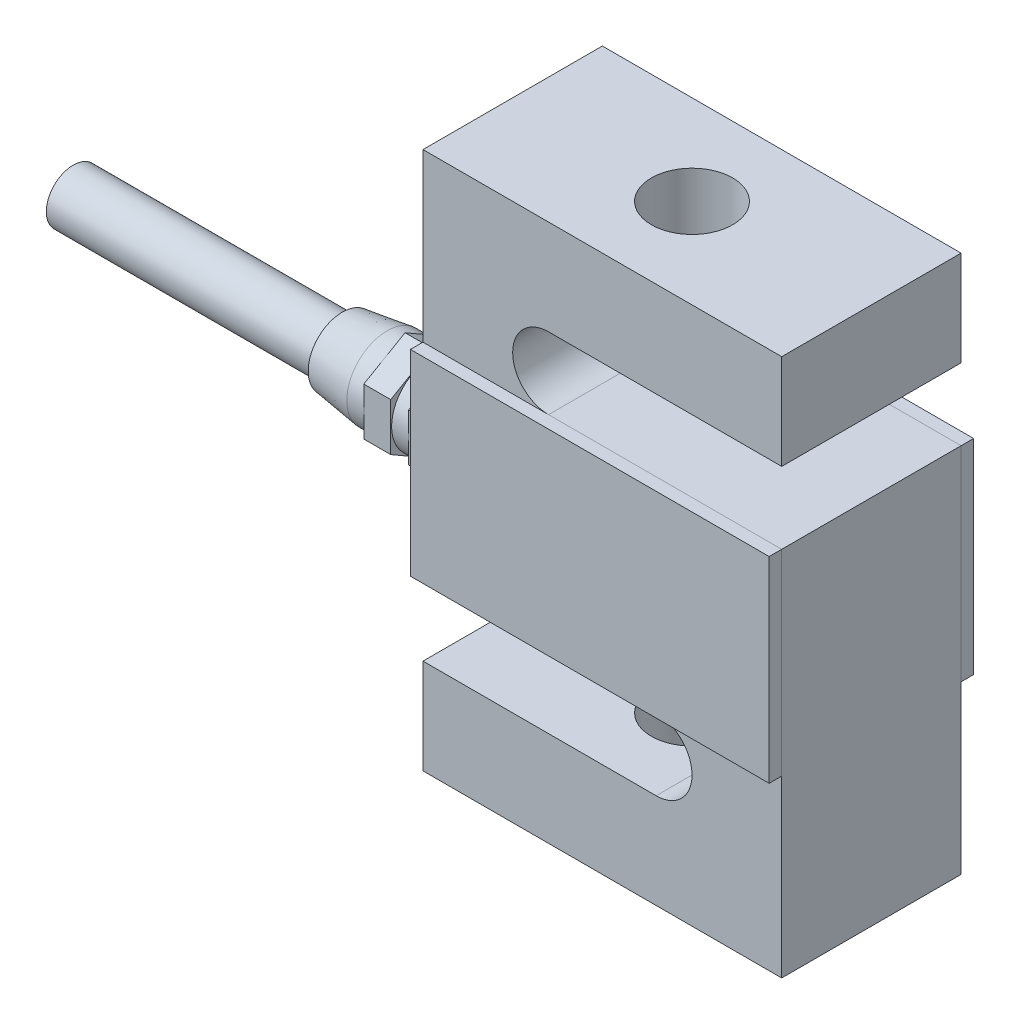
SolidWorks part; units mm, degrees
ref_plane "Front Plane" through (0, 0, 0) normal (0, 0, 1) x (1, 0, 0)
ref_plane "Top Plane" through (0, 0, 0) normal (0, 1, 0) x (1, 0, 0)
ref_plane "Right Plane" through (0, 0, 0) normal (1, 0, 0) x (0, 0, -1)
sketch "Sketch1" plane through (0, 0, 0) normal (0, 0, 1) x (1, 0, 0)
  line L0 (-25.4, -38.1) -> (25.4, -38.1)
  line L1 (25.4, -38.1) -> (25.4, 14.478)
  line L2 (25.4, 38.1) -> (-25.4, 38.1)
  line L3 (-25.4, 38.1) -> (-25.4, -14.478)
  line L4 (-25.4, -14.478) -> (7.62, -14.478)
  line L5 (-25.4, -24.638) -> (7.62, -24.638)
  line L6 (-69.5262, 0) -> (58.1333, 0) construction
  line L7 (7.62, -14.478) -> (7.62, -24.638) construction
  line L8 (-25.4, -24.638) -> (-25.4, -38.1)
  line L9 (-7.62, 24.638) -> (25.4, 24.638)
  line L10 (-7.62, 14.478) -> (25.4, 14.478)
  line L11 (25.4, 24.638) -> (25.4, 38.1)
  line L12 (-7.62, 24.638) -> (-7.62, 14.478) construction
  arc A0 (7.62, -24.638) -> (7.62, -14.478) centre (7.62, -19.558) ccw
  arc A1 (-7.62, 24.638) -> (-7.62, 14.478) centre (-7.62, 19.558) ccw
  dimension "D1" = 50.8
  dimension "D2" = 76.2
  dimension "D3" = 38.1
  dimension "D4" = 10.16
  dimension "D5" = 13.462
  dimension "D6" = 17.78
  dimension "D7" = 25.4
extrude "Extrude1" add sketch "Sketch1" along normal mid plane 25.4
hole_wizard "1/2-20 Tapped Hole1" positions "3DSketch2" profile "Sketch9" tap size "1/2-20" standard "ANSI Inch"
sketch3d "3DSketch2"
  point P0 (0, 38.1, 0)
sketch "Sketch9" plane through (0, 38.1, 0) normal (1, 0, 0) x (0, 0, 1)
  line L0 (0, 0) -> (0, 13.462)
  line L1 (0, 13.462) -> (5.7544, 13.462)
  line L2 (5.7544, 13.462) -> (5.7544, 0)
  line L5 (5.7544, 0) -> (0, 0)
  line L11 (0, -6.35) -> (0, 107.95) construction
  dimension "Thru Tap Drill Dia." = 11.5087
  dimension "Thru Tap Drill Depth" = 13.462
cosmetic thread "Hole Thread1" parameters "D2"=12.7
mirror "Mirror1" about plane through (0, 0, 0) normal (0, 1, 0) of "1/2-20 Tapped Hole1"
sketch "Sketch5" plane through (0, 0, 12.7) normal (0, 0, 1) x (1, 0, 0)
  line L0 (25.4, 14.478) -> (-7.62, 14.478) construction
  line L1 (25.4, 14.478) -> (-25.4, 14.478)
  line L2 (25.4, 14.478) -> (25.4, -13.335)
  line L3 (25.4, -13.335) -> (-25.4, -13.335)
  line L4 (-25.4, 14.478) -> (-25.4, -13.335)
  line L5 (-25.4, 38.1) -> (-25.4, -14.478) construction
extrude "Extrude5" add sketch "Sketch5" along normal blind 1.778 separate body
sketch "Sketch7" plane through (0, 0, -12.7) normal (0, 0, -1) x (-1, 0, 0)
  line L0 (25.4, -14.478) -> (-7.62, -14.478) construction
  line L1 (-25.4, 14.478) -> (25.4, 14.478)
  line L2 (-25.4, 14.478) -> (-25.4, -14.478)
  line L3 (-25.4, -14.478) -> (25.4, -14.478)
  line L4 (25.4, 14.478) -> (25.4, -14.478)
extrude "Extrude6" add sketch "Sketch7" along normal blind 1.778 separate body
sketch "Sketch10" plane through (-25.4, 0, 0) normal (-1, 0, 0) x (0, 0, 1)
  line L0 (0, 0) -> (5.08, 0) construction
  line L1 (5.08, 0) -> (5.08, 6.7458) construction
  line L2 (5.08, 6.7458) -> (-0.762, 3.3729)
  line L3 (-0.762, 3.3729) -> (-0.762, -3.3729)
  line L4 (-0.762, -3.3729) -> (5.08, -6.7458)
  line L5 (5.08, -6.7458) -> (10.922, -3.3729)
  line L6 (10.922, -3.3729) -> (10.922, 3.3729)
  line L7 (10.922, 3.3729) -> (5.08, 6.7458)
  circle A0 centre (5.08, 0) radius 5.842 construction
  dimension "D1" = 11.684
  dimension "D2" = 5.08
extrude "Boss-Extrude1" add sketch "Sketch10" along normal blind 10.16
ref_plane "Plane1" through (-29.21, 0, 0) normal (-1, 0, 0) x (0, 0, 1)
sketch "Sketch11" plane through (-29.21, 0, 0) normal (-1, 0, 0) x (0, 0, 1)
  line L0 (5.08, 6.7458) -> (5.08, 0) construction
  line L1 (5.08, 0) -> (0, 0) construction
  circle A0 centre (5.08, 0) radius 5.715
  circle A1 centre (5.08, 0) radius 6.7458
  dimension "D1" = 11.43
extrude "Cut-Extrude1" cut sketch "Sketch11" along normal offset from surface (2.54 mm away) 3.81 up to face at (-35.56, 0, 5.08)
sketch "Sketch12" plane through (0, 0, 0) normal (0, 1, 0) x (1, 0, 0)
  line L0 (-35.56, -5.08) -> (-82.55, -5.08) construction
  line L1 (-44.45, -0.254) -> (-44.45, -1.27)
  line L2 (-44.45, -1.27) -> (-82.55, -1.27)
  line L3 (-35.56, 0.635) -> (-38.1, 0.635)
  line L4 (-35.56, -5.08) -> (-35.56, 0.762) construction
  line L5 (-29.21, 0.635) -> (-31.75, 0.635) construction
  line L6 (-38.1, 0.635) -> (-44.45, -0.254)
  line L7 (-82.55, -1.27) -> (-82.55, -5.08)
  line L8 (-82.55, -5.08) -> (-35.56, -5.08)
  line L9 (-35.56, 0.635) -> (-35.56, -5.08)
  dimension "D1" = 2.54
  dimension "D2" = 4.826
  dimension "D3" = 6.35
  dimension "D4" = 3.81
  dimension "D5" = 38.1
revolve "Revolve1" add sketch "Sketch12" angle 360 about L0
equation "\"A\"= 1"
equation "\"B\" = 3"
equation "\"C\"= 2"
equation "\"D2@Sketch1\"=\"B\""
equation "\"D1@Sketch1\"=\"C\""
equation "\"D1@Extrude1\"=\"A\""
equation "\"D3@Sketch1\"=\"B\"/2"
equation "\"D7@Sketch1\"=\"C\"/2"
